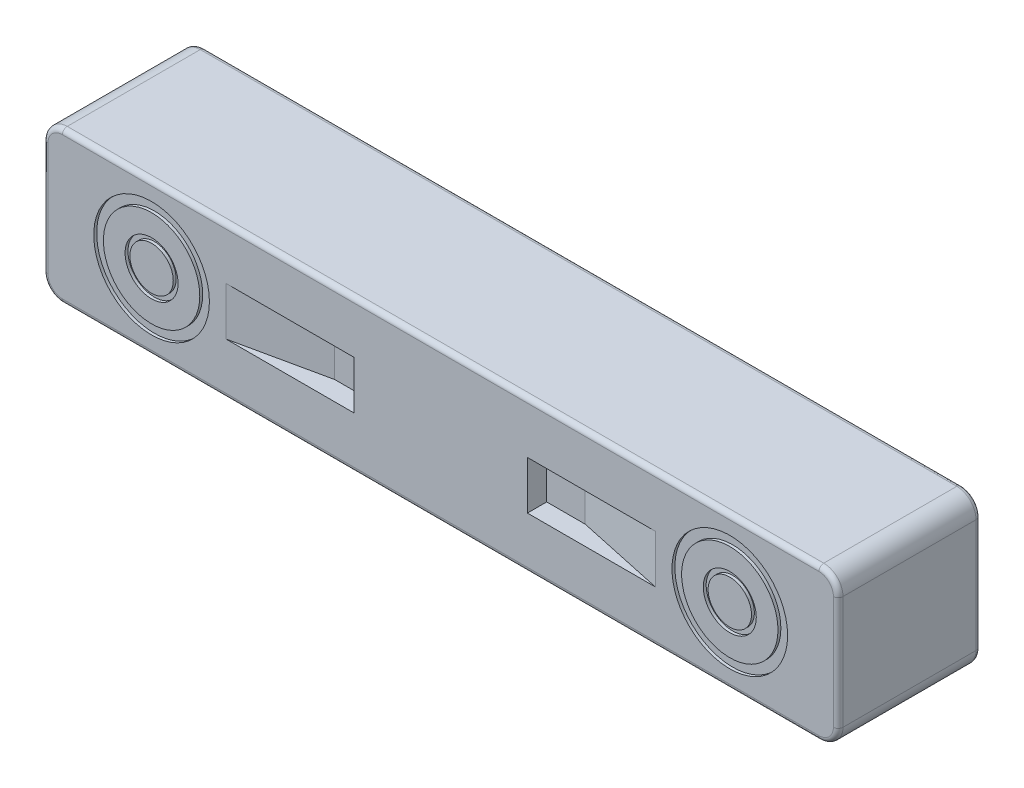
SolidWorks part; units mm, degrees
material "聚脂树脂"
ref_plane "前视基准面" through (0, 0, 0) normal (0, 0, 1) x (1, 0, 0)
ref_plane "上视基准面" through (0, 0, 0) normal (0, 1, 0) x (1, 0, 0)
ref_plane "右视基准面" through (0, 0, 0) normal (1, 0, 0) x (0, 0, -1)
sketch "草图1" plane through (0, 0, 0) normal (0, 0, 1) x (1, 0, 0)
  line L1 (-82.5, -15.75) -> (82.5, -15.75)
  line L2 (-82.5, -15.75) -> (-82.5, 15.75)
  line L3 (-82.5, 15.75) -> (82.5, 15.75)
  line L4 (82.5, -15.75) -> (82.5, 15.75)
  line L5 (-82.5, -15.75) -> (82.5, 15.75) construction
  line L6 (-82.5, 15.75) -> (82.5, -15.75) construction
  point P0 (0, 0)
extrude "凸台-拉伸1" add sketch "草图1" along normal blind 29.6
sketch "草图2" plane through (0, 0, 29.6) normal (0, 0, 1) x (1, 0, 0)
  line L0 (0, -16.28) -> (0, 16.28) construction
  circle A1 centre (-60, 0) radius 12
  circle A2 centre (-60, 0) radius 10
  circle A3 centre (-60, 0) radius 5.5
  circle A4 centre (-60, 0) radius 4.5
  circle A5 centre (60, 0) radius 4.5
  circle A6 centre (60, 0) radius 5.5
  circle A7 centre (60, 0) radius 10
  circle A8 centre (60, 0) radius 12
  dimension "D1" = 4.5
  dimension "D2" = 60
  dimension "D3" = 2
  dimension "D4" = 1
extrude "切除-拉伸1" cut sketch "草图2" against normal blind 0.6 contours A1 A2 | A3 A4 | A8 A7 | A6 A5
fillet "圆角1" radius 4 4 edges at (82.5, -15.75, 14.8) (82.5, 15.75, 14.8) (-82.5, -15.75, 14.8) (-82.5, 15.75, 14.8)
fillet "圆角2" radius 1 16 edges at (81.3284, 14.5784, 0) (81.3284, -14.5784, 0) (-81.3284, -14.5784, 0) (-81.3284, 14.5784, 0) (81.3284, 14.5784, 29.6) (81.3284, -14.5784, 29.6) (-81.3284, -14.5784, 29.6) (-81.3284, 14.5784, 29.6) (-82.5, 0, 0) (0, -15.75, 0) (82.5, 0, 0) (0, 15.75, 0) (82.5, 0, 29.6) (-82.5, 0, 29.6) (0, -15.75, 29.6) (0, 15.75, 29.6)
sketch "草图3" plane through (0, 0, 29.6) normal (0, 0, 1) x (1, 0, 0)
  line L1 (-26, 5) -> (-18, 5)
  line L2 (-26, 5) -> (-26, -5)
  line L3 (-26, -5) -> (-18, -5)
  line L4 (-18, 5) -> (-18, -5)
  line L6 (-78.5, 15.75) -> (78.5, 15.75) construction
  line L7 (0, -16.28) -> (0, 16.28) construction
  line L8 (18, 5) -> (18, -5)
  line L9 (26, -5) -> (18, -5)
  line L10 (26, 5) -> (26, -5)
  line L11 (26, 5) -> (18, 5)
  dimension "D1" = 10.75
  dimension "D2" = 18
extrude "切除-拉伸2" cut sketch "草图3" against normal blind 4
sketch "草图4" plane through (0, 5, 0) normal (0, -1, 0) x (1, 0, 0)
  line L8 (26, 25.6) -> (44.5742, 29.6)
  line L9 (78.5, 29.6) -> (-78.5, 29.6) construction
  line L10 (26, 25.6) -> (26, 29.6)
  line L11 (26, 29.6) -> (44.5742, 29.6)
  line L12 (0, -16.28) -> (0, 16.28) construction
  line L13 (-26, 29.6) -> (-44.5742, 29.6)
  line L14 (-26, 25.6) -> (-26, 29.6)
  line L15 (-26, 25.6) -> (-44.5742, 29.6)
extrude "切除-拉伸3" cut sketch "草图4" along normal blind 10
scale "缩放比例1" bodies to scale 109 scale about centroid uniform scaling yes scale factor 0.5
